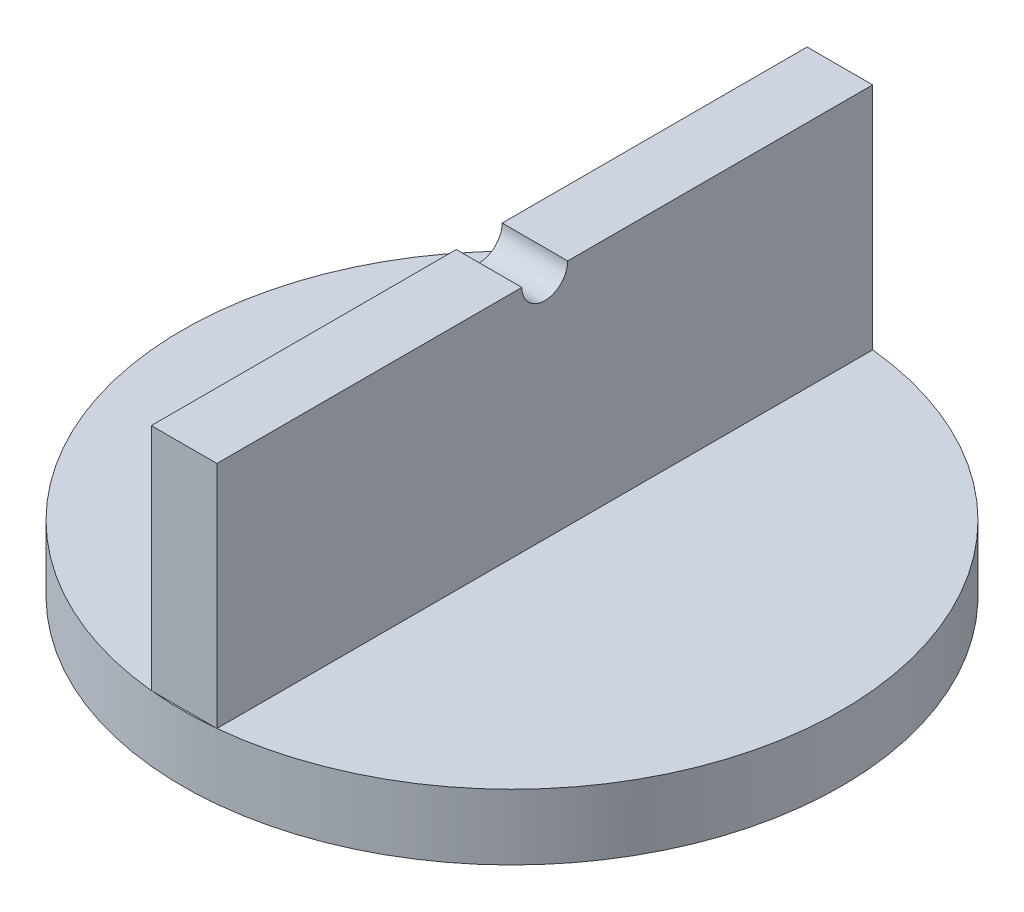
SolidWorks part; units mm, degrees
material "Gray Cast Iron"
ref_plane "Front Plane" through (0, 0, 0) normal (0, 0, 1) x (1, 0, 0)
ref_plane "Top Plane" through (0, 0, 0) normal (0, 1, 0) x (1, 0, 0)
ref_plane "Right Plane" through (0, 0, 0) normal (1, 0, 0) x (0, 0, -1)
sketch "Sketch1" plane through (0, 0, 0) normal (1, 0, 0) x (0, 0, -1)
  line L0 (-3.5, 17.5) -> (-50, 17.5)
  line L1 (50, 17.5) -> (3.5, 17.5)
  line L2 (50, 17.5) -> (50, -17.5)
  line L3 (50, -17.5) -> (-50, -17.5)
  line L4 (-50, 17.5) -> (-50, -17.5)
  line L5 (50, 17.5) -> (-50, -17.5) construction
  line L6 (50, -17.5) -> (-50, 17.5) construction
  arc A0 (-3.5, 17.5) -> (3.5, 17.5) centre (0, 17.5) ccw
  point P0 (0, 0)
  dimension "D3" = 7
  dimension "D1" = 100
  dimension "D2" = 35
extrude "Boss-Extrude1" add sketch "Sketch1" along normal mid plane 10
sketch "Sketch2" plane through (0, -17.5, 0) normal (0, -1, 0) x (1, 0, 0)
  circle A0 centre (0, 0) radius 50.2494
extrude "Boss-Extrude2" add sketch "Sketch2" along normal blind 10
